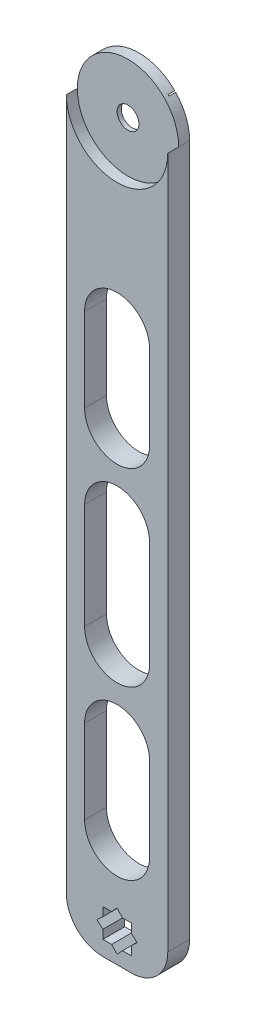
SolidWorks part; units mm, degrees
ref_plane "Plan de face" through (0, 0, 0) normal (0, 0, 1) x (1, 0, 0)
ref_plane "Plan de dessus" through (0, 0, 0) normal (0, 1, 0) x (1, 0, 0)
ref_plane "Plan de droite" through (0, 0, 0) normal (1, 0, 0) x (0, 0, -1)
sketch "Esquisse1" plane through (0, 0, 0) normal (0, 0, 1) x (1, 0, 0)
  line L1 (-12.0899, 21.2113) -> (15.7601, 21.2113)
  line L2 (-12.0899, 21.2113) -> (-12.0899, -178.7887)
  line L3 (-12.0899, -178.7887) -> (15.7601, -178.7887)
  line L4 (15.7601, 21.2113) -> (15.7601, -178.7887)
  arc A1 (15.7601, 21.2113) -> (-12.0899, 21.2113) centre (1.8351, 21.2113) ccw
  dimension "D1" = 27.85
  dimension "D2" = 200
extrude "Boss.-Extru.2" add sketch "Esquisse1" along normal blind 6 contours L4 L1 L2 L3 | L1 A1
sketch "Esquisse3" plane through (0, 0, 6) normal (0, 0, 1) x (1, 0, 0)
  line L0 (15.7601, 21.2113) -> (15.7601, -178.7887) construction
  line L1 (-12.0899, -178.7887) -> (15.7601, -178.7887) construction
  line L2 (4.4332, -169.2887) -> (4.4332, -172.2887)
  circle A0 centre (1.8351, -170.7887) radius 3
  dimension "D1" = 6
  dimension "D2" = 13.925
  dimension "D3" = 8
  dimension "D4" = 3
extrude "Enlèv. mat.-Extru.1" cut sketch "Esquisse3" against normal blind 6
sketch "Esquisse4" plane through (0, 0, 6) normal (0, 0, 1) x (1, 0, 0)
  circle A0 centre (1.8351, 21.2113) radius 13.925
extrude "Enlèv. mat.-Extru.2" cut sketch "Esquisse4" against normal blind 3
sketch "Esquisse5" plane through (0, 0, 3) normal (0, 0, 1) x (1, 0, 0)
  circle A0 centre (1.8351, 21.2113) radius 3
  dimension "D1" = 6
extrude "Enlèv. mat.-Extru.3" cut sketch "Esquisse5" against normal blind 3
sketch "Esquisse6" plane through (0, 0, 6) normal (0, 0, 1) x (1, 0, 0)
  line L0 (15.7601, 21.2113) -> (15.7601, -178.7887) construction
  line L1 (-7.0899, -27.7887) -> (10.7601, -27.7887)
  line L2 (-7.0899, -27.7887) -> (-7.0899, -50.7887)
  line L3 (-7.0899, -50.7887) -> (10.7601, -50.7887)
  line L4 (10.7601, -27.7887) -> (10.7601, -50.7887)
  line L5 (-7.0899, -73.7887) -> (10.7601, -73.7887)
  line L6 (-7.0899, -73.7887) -> (-7.0899, -102.7887)
  line L7 (-7.0899, -102.7887) -> (10.7601, -102.7887)
  line L8 (10.7601, -73.7887) -> (10.7601, -102.7887)
  line L9 (-7.0899, -125.7887) -> (10.7601, -125.7887)
  line L10 (-7.0899, -125.7887) -> (-7.0899, -148.7887)
  line L11 (-7.0899, -148.7887) -> (10.7601, -148.7887)
  line L12 (10.7601, -125.7887) -> (10.7601, -148.7887)
  line L13 (-12.0899, 21.2113) -> (-12.0899, -178.7887) construction
  line L14 (-12.0899, -178.7887) -> (15.7601, -178.7887) construction
  arc A0 (10.7601, -27.7887) -> (-7.0899, -27.7887) centre (1.8351, -27.7887) ccw
  arc A1 (-7.0899, -50.7887) -> (10.7601, -50.7887) centre (1.8351, -50.7887) ccw
  arc A2 (-7.0899, -73.7887) -> (10.7601, -73.7887) centre (1.8351, -73.7887) cw
  arc A3 (-7.0899, -102.7887) -> (10.7601, -102.7887) centre (1.8351, -102.7887) ccw
  arc A4 (10.7601, -125.7887) -> (-7.0899, -125.7887) centre (1.8351, -125.7887) ccw
  arc A5 (-7.0899, -148.7887) -> (10.7601, -148.7887) centre (1.8351, -148.7887) ccw
  dimension "D1" = 5
  dimension "D2" = 5
  dimension "D3" = 5
  dimension "D4" = 5
  dimension "D5" = 5
  dimension "D6" = 5
  dimension "D7" = 23
  dimension "D8" = 23
  dimension "D9" = 23
  dimension "D10" = 23
  dimension "D11" = 29
  dimension "D12" = 30
extrude "Enlèv. mat.-Extru.4" cut sketch "Esquisse6" against normal blind 10 contours L1 A0 | L4 L1 L2 L3 | L3 A1 | A2 L5 | L8 L5 L6 L7 | L7 A3 | L9 A4 | L12 L9 L10 L11 | L11 A5
fillet "Congé1" radius 10 1 edges at (-12.0899, -178.7887, 3)
fillet "Congé2" radius 10 1 edges at (15.7601, -178.7887, 3)
sketch "Esquisse7" plane through (0, 0, 0) normal (0, 0, -1) x (-1, 0, 0)
  circle A0 centre (-1.8351, 21.2113) radius 6.425
extrude "Enlèv. mat.-Extru.5" [suppressed] cut sketch "Esquisse7" against normal blind 1
sketch "Esquisse8" [suppressed] plane through (0, 0, 1) normal (0, 0, -1) x (-1, 0, 0)
  circle A0 centre (-1.8351, 21.2113) radius 5.56
extrude "Enlèv. mat.-Extru.6" [suppressed] cut sketch "Esquisse8" against normal blind 0.8
sketch "Esquisse9" plane through (0, 0, 0) normal (0, 0, -1) x (-1, 0, 0)
  line L1 (-11.9301, 31.0613) -> (8.2699, 31.0613)
  line L2 (-11.9301, 31.0613) -> (-11.9301, -9.2387)
  line L3 (-11.9301, -9.2387) -> (8.2699, -9.2387)
  line L4 (8.2699, 31.0613) -> (8.2699, -9.2387)
  line L6 (-15.7601, 21.2113) -> (-15.7601, -168.7887) construction
  circle A0 centre (-1.8351, 21.2113) radius 3 construction
  dimension "D1" = 20.2
  dimension "D2" = 40.3
  dimension "D3" = 9.85
  dimension "D4" = 3.83
extrude "Enlèv. mat.-Extru.7" cut sketch "Esquisse9" against normal blind 1.85
sketch "Esquisse11" plane through (0, 0, 6) normal (0, 0, 1) x (1, 0, 0)
  line L0 (-2.0604, -166.8932) -> (5.7305, -166.8932)
  line L1 (-2.0604, -166.8932) -> (-2.0604, -174.6841)
  line L2 (5.7305, -166.8932) -> (5.7305, -174.6841)
  line L3 (-2.0604, -174.6841) -> (5.7305, -174.6841)
  line L4 (1.8351, -165.2796) -> (0.3396, -166.8932)
  line L5 (1.8351, -165.2796) -> (3.3305, -166.8932)
  line L6 (-3.674, -170.7887) -> (-2.0604, -169.2932)
  line L7 (-3.674, -170.7887) -> (-2.0604, -172.2841)
  line L8 (1.8351, -176.2977) -> (0.3396, -174.6841)
  line L9 (1.8351, -176.2977) -> (3.3305, -174.6841)
  line L10 (5.7305, -169.2932) -> (7.3441, -170.7887)
  line L11 (5.7305, -172.2841) -> (7.3441, -170.7887)
  line L12 (4.4332, -169.2887) -> (4.4332, -172.2887)
  circle A0 centre (1.8351, -170.7887) radius 3
  arc A1 (4.4332, -169.2887) -> (4.4332, -172.2887) centre (1.8351, -170.7887) ccw construction
  circle A2 centre (1.8351, -170.7887) radius 5.509
  arc M17 (4.4332, -172.2887) -> (4.4332, -169.2887) centre (1.8351, -170.7887) cw
  line M18 (4.4332, -169.2887) -> (4.4332, -172.2887)
  dimension "D11" = 2.2
  dimension "D6" = 2.2
  dimension "D2" = 2.2
  dimension "D3" = 2.2
  dimension "D4" = 2.4
  dimension "D5" = 2.4
  dimension "D7" = 2.4
  dimension "D8" = 2.4
  dimension "D9" = 2.4
  dimension "D10" = 2.2
  dimension "D12" = 2.2
  dimension "D15" = 3
  dimension "D16" = 0
extrude "Enlèv. mat.-Extru.8" cut sketch "Esquisse11" against normal blind 10 contours L6 L7 L1 | L1 L3 L2 L0 A0 M17 | L5 L4 L0 | L2 L11 L10 | L8 L9 L3 | A0 M18
